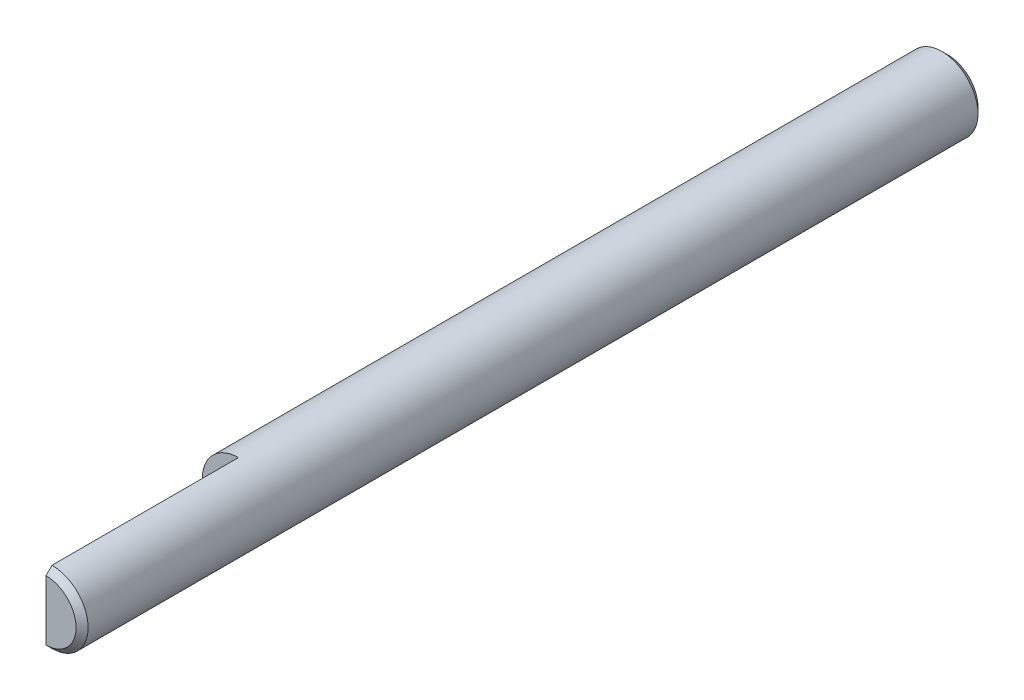
SolidWorks part; units mm, degrees
ref_plane "Front" through (0, 0, 0) normal (0, 0, 1) x (1, 0, 0)
ref_plane "Top" through (0, 0, 0) normal (0, 1, 0) x (1, 0, 0)
ref_plane "Right" through (0, 0, 0) normal (1, 0, 0) x (0, 0, -1)
sketch "Sketch1" plane through (0, 0, 0) normal (0, 0, 1) x (1, 0, 0)
  circle A0 centre (0, 0) radius 3
  dimension "D1" = 6
extrude "Boss-Extrude1" add sketch "Sketch1" along normal blind 75
chamfer "Chamfer1" distance 0.5 angle 45 2 edges at (3, 0, 0) (3, 0, 75)
sketch "Sketch2" plane through (0, 0, 75) normal (0, 0, 1) x (1, 0, 0)
  line L0 (0, -3) -> (0, 3)
  arc A0 (0, 3) -> (0, -3) centre (0, 0) ccw
  circle A2 centre (0, 0) radius 3 construction
  point P1 (0, 0)
  dimension "D1" = 0
extrude "Cut-Extrude2" cut sketch "Sketch2" against normal blind 16
